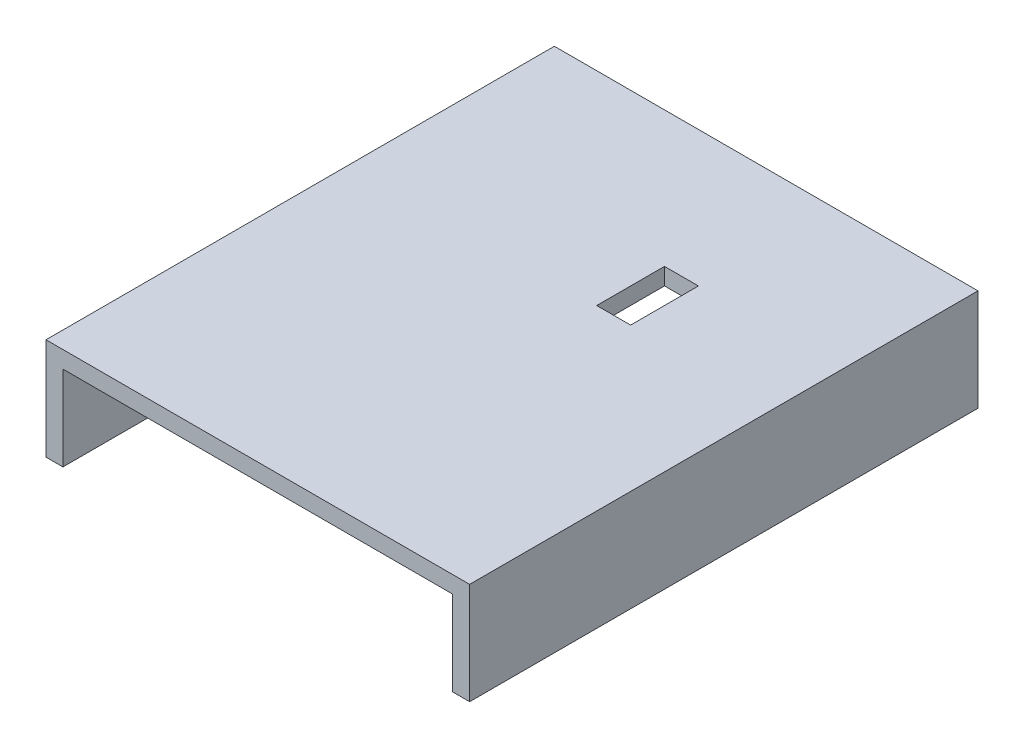
SolidWorks part; units mm, degrees
ref_plane "Front Plane" through (0, 0, 0) normal (0, 0, 1) x (1, 0, 0)
ref_plane "Top Plane" through (0, 0, 0) normal (0, 1, 0) x (1, 0, 0)
ref_plane "Right Plane" through (0, 0, 0) normal (1, 0, 0) x (0, 0, -1)
sketch "Sketch1" plane through (0, 0, 0) normal (0, 1, 0) x (1, 0, 0)
  line L1 (-125, -150) -> (125, -150)
  line L2 (-125, -150) -> (-125, 150)
  line L3 (-125, 150) -> (125, 150)
  line L4 (125, -150) -> (125, 150)
  line L5 (-125, -150) -> (125, 150) construction
  line L6 (-125, 150) -> (125, -150) construction
  line L7 (20, 30) -> (40, 30)
  line L8 (20, 30) -> (20, 70)
  line L9 (20, 70) -> (40, 70)
  line L10 (40, 30) -> (40, 70)
  line L11 (20, 30) -> (40, 70) construction
  line L12 (20, 70) -> (40, 30) construction
  point P0 (0, 0)
  point P5 (0, 0)
  point P7 (0, 0)
  point P12 (0, 0)
  point P13 (0, 0)
  point P14 (0, 0)
  point P15 (0, 0)
  point P16 (0, 0)
  point P17 (30, 30)
  point P18 (20, 50)
  dimension "D1" = 250
  dimension "D2" = 300
  dimension "D3" = 40
  dimension "D4" = 20
  dimension "D5" = 100
  dimension "D6" = 30
extrude "Boss-Extrude1" add sketch "Sketch1" along normal blind 10
sketch "Sketch2" plane through (0, 0, 0) normal (0, -1, 0) x (1, 0, 0)
  line L0 (125, -150) -> (-125, -150) construction
  line L1 (125, 150) -> (115, 150)
  line L2 (125, 150) -> (125, -150)
  line L3 (125, -150) -> (115, -150)
  line L4 (115, 150) -> (115, -150)
  line L5 (0, 0) -> (0, 112.9953) construction
  line L6 (-125, -150) -> (-115, -150)
  line L7 (-115, 150) -> (-115, -150)
  line L8 (-125, 150) -> (-115, 150)
  line L9 (-125, 150) -> (-125, -150)
  dimension "D1" = 10
extrude "Boss-Extrude2" add sketch "Sketch2" along normal blind 50
